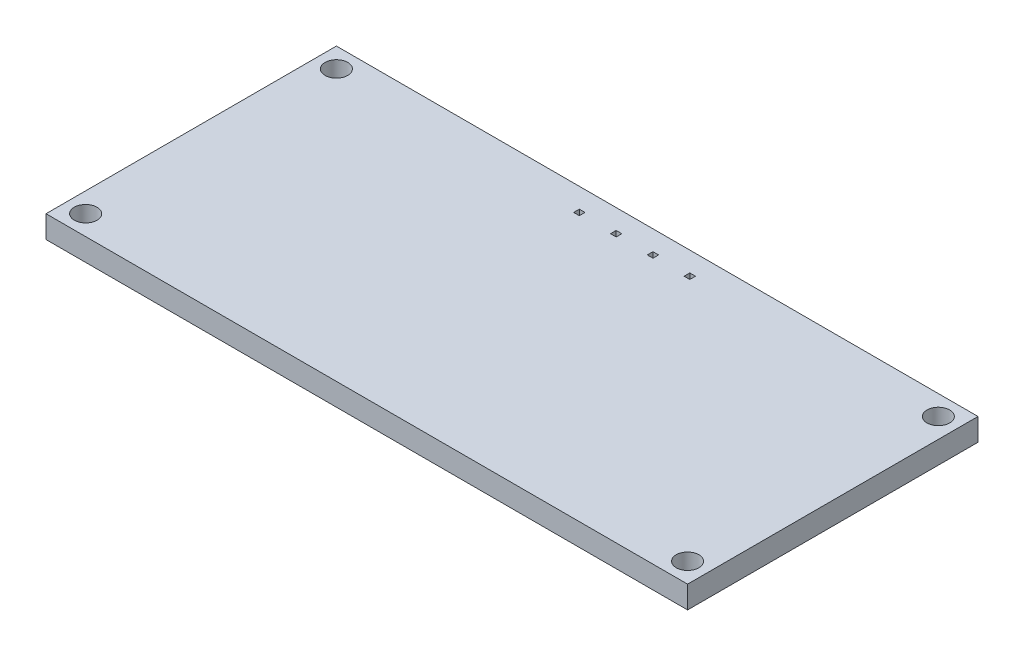
SolidWorks part; units mm, degrees
ref_plane "Alzado" through (0, 0, 0) normal (0, 0, 1) x (1, 0, 0)
ref_plane "Planta" through (0, 0, 0) normal (0, 1, 0) x (1, 0, 0)
ref_plane "Vista lateral" through (0, 0, 0) normal (1, 0, 0) x (0, 0, -1)
sketch "Croquis1" plane through (0, 0, 0) normal (0, 1, 0) x (1, 0, 0)
  line L1 (0, 0) -> (45.31, 0)
  line L2 (0, 0) -> (0, 20.51)
  line L3 (0, 20.51) -> (45.31, 20.51)
  line L4 (45.31, 0) -> (45.31, 20.51)
  circle A0 centre (1.4, 19.11) radius 0.8
  circle A1 centre (43.91, 19.11) radius 0.8
  circle A2 centre (1.4, 1.4) radius 0.8
  circle A3 centre (43.91, 1.4) radius 0.8
  point P13 (1.4, 19.91)
  point P14 (0.6, 19.11)
  point P15 (43.91, 0.6)
  point P19 (44.71, 19.11)
  dimension "D3" = 1.6
  dimension "D1" = 45.31
  dimension "D2" = 20.51
  dimension "D4" = 0.6
  dimension "D5" = 0.6
  dimension "D6" = 0.6
  dimension "D7" = 0.6
extrude "Saliente-Extruir1" add sketch "Croquis1" along normal blind 1.58
sketch "Croquis2" plane through (0, 0, 0) normal (0, -1, 0) x (1, 0, 0)
  line L0 (21.555, -18.71) -> (21.555, -19.11)
  line L1 (18.555, -18.71) -> (18.955, -18.71)
  line L2 (18.555, -18.71) -> (18.555, -19.11)
  line L3 (18.555, -19.11) -> (18.955, -19.11)
  line L4 (18.955, -18.71) -> (18.955, -19.11)
  line L5 (21.155, -18.71) -> (21.155, -19.11)
  line L6 (21.155, -18.71) -> (21.555, -18.71)
  line L7 (21.155, -19.11) -> (21.555, -19.11)
  line L8 (24.155, -18.71) -> (24.155, -19.11)
  line L9 (23.755, -18.71) -> (23.755, -19.11)
  line L10 (23.755, -18.71) -> (24.155, -18.71)
  line L11 (23.755, -19.11) -> (24.155, -19.11)
  line L12 (26.755, -18.71) -> (26.755, -19.11)
  line L13 (26.355, -18.71) -> (26.355, -19.11)
  line L14 (26.355, -18.71) -> (26.755, -18.71)
  line L15 (26.355, -19.11) -> (26.755, -19.11)
  line L16 (18.555, -18.71) -> (26.755, -18.71) construction
  line L17 (45.31, -20.51) -> (0, -20.51) construction
  point P5 (22.655, -18.71)
  point P17 (22.655, -20.51)
  dimension "D1" = 0.4
  dimension "D3" = 1.4
  dimension "D4" = 2.2
  dimension "D2" = 4
extrude "Cortar-Extruir1" cut sketch "Croquis2" against normal through all
